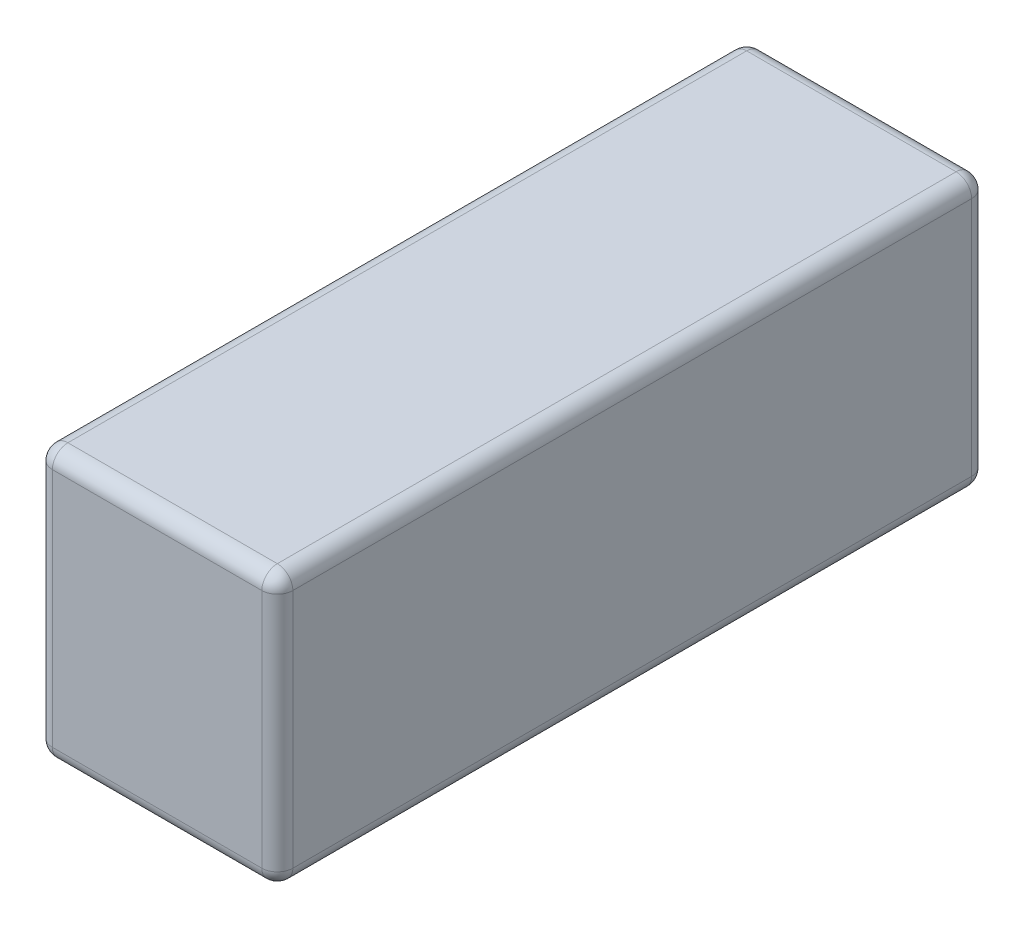
SolidWorks part; units mm, degrees
ref_plane "Alzado" through (0, 0, 0) normal (0, 0, 1) x (1, 0, 0)
ref_plane "Planta" through (0, 0, 0) normal (0, 1, 0) x (1, 0, 0)
ref_plane "Vista lateral" through (0, 0, 0) normal (1, 0, 0) x (0, 0, -1)
sketch "Croquis1" plane through (0, 0, 0) normal (0, 0, 1) x (1, 0, 0)
  line L1 (-15.5, 17.5) -> (15.5, 17.5)
  line L2 (-15.5, 17.5) -> (-15.5, -17.5)
  line L3 (-15.5, -17.5) -> (15.5, -17.5)
  line L4 (15.5, 17.5) -> (15.5, -17.5)
  line L5 (-15.5, 17.5) -> (15.5, -17.5) construction
  line L6 (-15.5, -17.5) -> (15.5, 17.5) construction
  point P0 (0, 0)
  dimension "D1" = 35
  dimension "D2" = 31
extrude "Saliente-Extruir1" add sketch "Croquis1" along normal blind 91.5
fillet "Redondeo1" radius 2 12 edges at (0, -17.5, 91.5) (-15.5, 0, 91.5) (0, 17.5, 91.5) (15.5, 0, 91.5) (-15.5, -17.5, 45.75) (-15.5, 17.5, 45.75) (-15.5, 0, 0) (0, -17.5, 0) (15.5, -17.5, 45.75) (15.5, 0, 0) (15.5, 17.5, 45.75) (0, 17.5, 0)
